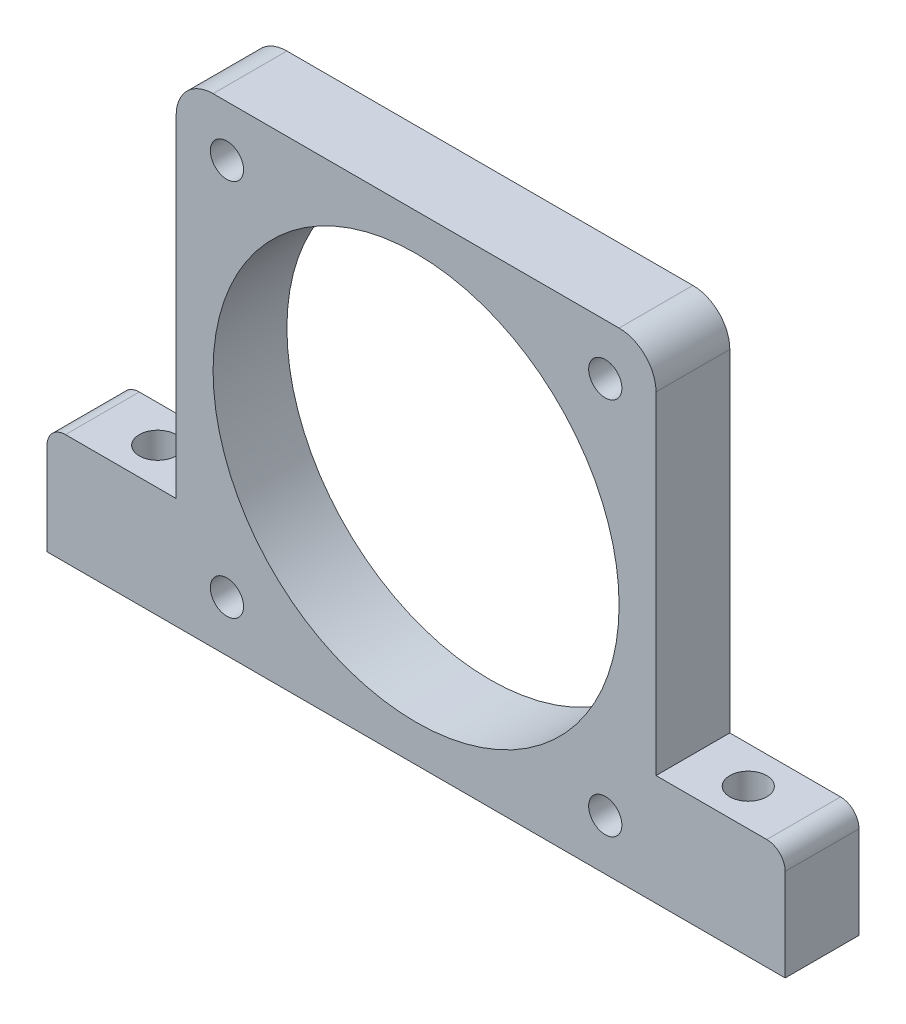
SolidWorks part; units mm, degrees
ref_plane "Front Plane" through (0, 0, 0) normal (0, 0, 1) x (1, 0, 0)
ref_plane "Top Plane" through (0, 0, 0) normal (0, 1, 0) x (1, 0, 0)
ref_plane "Right Plane" through (0, 0, 0) normal (1, 0, 0) x (0, 0, -1)
sketch "草圖1" plane through (0, 0, 0) normal (0, 0, 1) x (1, 0, 0)
  line L1 (-55, 65) -> (55, 65)
  line L2 (-65, 55) -> (-65, -65)
  line L3 (-65, -65) -> (65, -65)
  line L4 (65, 55) -> (65, -65)
  arc A0 (65, 55) -> (55, 65) centre (55, 55) ccw
  arc A3 (-65, 55) -> (-55, 65) centre (-55, 55) cw
  point P8 (65, 65)
  point P11 (65, -65)
  point P16 (-65, 65)
  dimension "D5" = 10
  dimension "D1" = 130
  dimension "D2" = 130
  dimension "D3" = 65
  dimension "D4" = 65
extrude "填料-伸長1" add sketch "草圖1" along normal blind 20 contours L1 A0 L4 L3 L2 A3
sketch "草圖2" plane through (0, 0, 0) normal (0, 0, 1) x (1, 0, 0)
  line L0 (-55, 65) -> (55, 65) construction
  line L2 (65, 55) -> (65, -65) construction
  circle A0 centre (51.25, 51.25) radius 4.5
  dimension "D1" = 9
  dimension "D3" = 13.75
  dimension "D2" = 13.75
extrude "除料-伸長2" cut sketch "草圖2" along normal through all
ref_plane "平面1" through (0, 0, 0) normal (0, 1, 0) x (1, 0, 0)
ref_plane "平面2" through (0, 0, 0) normal (1, 0, 0) x (0, 0, -1)
mirror "鏡射1" about plane through (0, 0, 0) normal (1, 0, 0) of "除料-伸長2"
mirror "鏡射2" about plane through (0, 0, 0) normal (0, 1, 0) of "鏡射1", "除料-伸長2"
sketch "草圖3" plane through (0, 0, 0) normal (0, 0, 1) x (1, 0, 0)
  line L0 (-55, 65) -> (55, 65) construction
  line L1 (65, 55) -> (65, -65) construction
  circle A0 centre (0, 0) radius 55
  dimension "D1" = 65
  dimension "D3" = 110
  dimension "D2" = 65
extrude "除料-伸長3" cut sketch "草圖3" along normal through all
sketch "草圖5" plane through (0, 0, 0) normal (0, 0, 1) x (1, 0, 0)
  line L1 (65, -65) -> (100, -65)
  line L2 (65, -65) -> (65, -35)
  line L3 (65, -35) -> (95, -35)
  line L4 (100, -65) -> (100, -40)
  arc A0 (100, -40) -> (95, -35) centre (95, -40) ccw
  point P7 (100, -35)
  dimension "D3" = 5
  dimension "D1" = 35
  dimension "D2" = 30
extrude "填料-伸長2" add sketch "草圖5" along normal blind 20
sketch "草圖6" plane through (0, -35, 0) normal (0, 1, 0) x (1, 0, 0)
  line L0 (95, -20) -> (65, -20) construction
  line L2 (65, -20) -> (65, 0) construction
  circle A0 centre (80, -10) radius 5
  dimension "D1" = 10
  dimension "D2" = 15
extrude "除料-伸長4" cut sketch "草圖6" against normal through all contours A0
mirror "鏡射3" about plane through (0, 0, 0) normal (1, 0, 0) of "填料-伸長2"
mirror "鏡射4" about plane through (0, 0, 0) normal (1, 0, 0) of "除料-伸長4"
sketch "定位销" plane through (0, 0, 0) normal (0, 0, -1) x (-1, 0, 0)
  line L1 (100, -65) -> (-100, -65) construction
  line L2 (65, 55) -> (65, -35) construction
  line L3 (55, 65) -> (-55, 65) construction
  line L4 (-65, 55) -> (-65, -35) construction
  circle A0 centre (59.84, -48.46) radius 2.5
  circle A1 centre (-59.84, 48.46) radius 2.5
  dimension "D1" = 5
  dimension "D3" = 16.54
  dimension "D4" = 5
  dimension "D5" = 5.16
  dimension "D6" = 16.54
  dimension "D2" = 5.16
extrude "除料-伸長5" cut sketch "定位销" against normal blind 10
